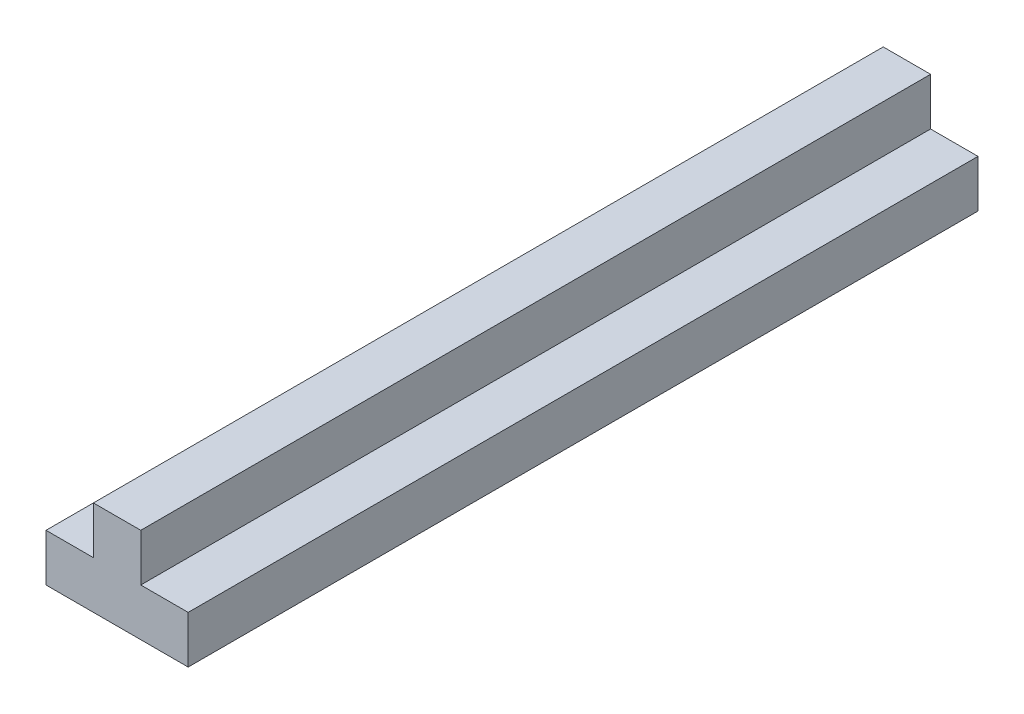
SolidWorks part; units mm, degrees
ref_plane "Front Plane" through (0, 0, 0) normal (0, 0, 1) x (1, 0, 0)
ref_plane "Top Plane" through (0, 0, 0) normal (0, 1, 0) x (1, 0, 0)
ref_plane "Right Plane" through (0, 0, 0) normal (1, 0, 0) x (0, 0, -1)
sketch "Sketch1" plane through (0, 0, 0) normal (0, 0, 1) x (1, 0, 0)
  line L0 (0, 0) -> (4.5, 0)
  line L1 (4.5, 0) -> (4.5, 3)
  line L2 (4.5, 3) -> (1.5, 3)
  line L3 (1.5, 3) -> (1.5, 6)
  line L4 (1.5, 6) -> (-1.5, 6)
  line L5 (-1.5, 6) -> (-1.5, 3)
  line L6 (-1.5, 3) -> (-4.5, 3)
  line L7 (-4.5, 3) -> (-4.5, 0)
  line L8 (-4.5, 0) -> (0, 0)
  dimension "D1" = 3
  dimension "D2" = 3
  dimension "D3" = 3
  dimension "D4" = 4.5
  dimension "D5" = 4.5
  dimension "D6" = 3
  dimension "D7" = 3
extrude "Boss-Extrude1" add sketch "Sketch1" along normal blind 50
